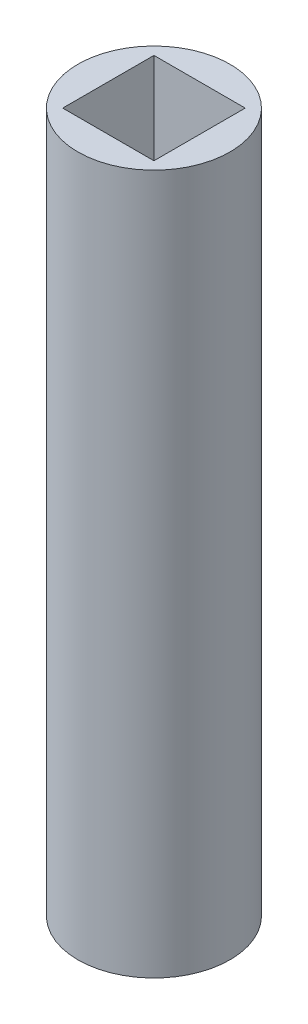
SolidWorks part; units mm, degrees
material "PLA"
ref_plane "Front" through (0, 0, 0) normal (0, 0, 1) x (1, 0, 0)
ref_plane "Top" through (0, 0, 0) normal (0, 1, 0) x (1, 0, 0)
ref_plane "Right" through (0, 0, 0) normal (1, 0, 0) x (0, 0, -1)
sketch "Sketch1" plane through (0, 0, 0) normal (0, 1, 0) x (1, 0, 0)
  circle A0 centre (0, 0) radius 15.875
  dimension "D1" = 31.75
extrude "Boss-Extrude1" add sketch "Sketch1" along normal blind 146.05
sketch "Sketch2" plane through (0, 146.05, 0) normal (0, 1, 0) x (1, 0, 0)
  line L1 (9.525, -9.525) -> (-9.525, -9.525)
  line L2 (9.525, -9.525) -> (9.525, 9.525)
  line L3 (9.525, 9.525) -> (-9.525, 9.525)
  line L4 (-9.525, -9.525) -> (-9.525, 9.525)
  line L5 (9.525, -9.525) -> (-9.525, 9.525) construction
  line L6 (9.525, 9.525) -> (-9.525, -9.525) construction
  point P0 (0, 0)
  dimension "D1" = 19.05
  dimension "D2" = 19.05
extrude "Cut-Extrude1" cut sketch "Sketch2" against normal blind 172.72
